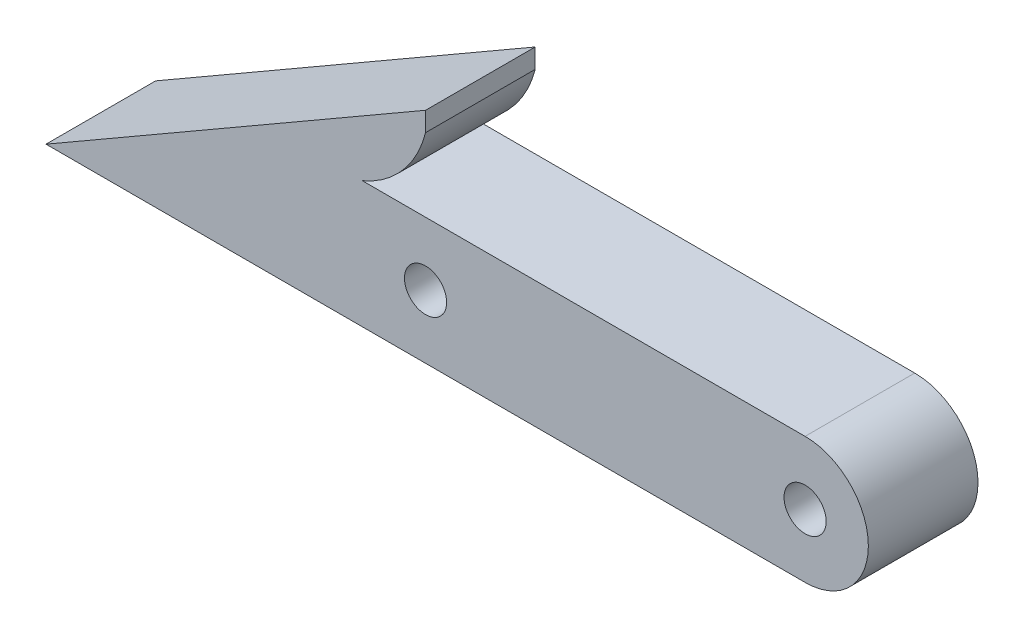
SolidWorks part; units mm, degrees
ref_plane "Front Plane" through (0, 0, 0) normal (0, 0, 1) x (1, 0, 0)
ref_plane "Top Plane" through (0, 0, 0) normal (0, 1, 0) x (1, 0, 0)
ref_plane "Right Plane" through (0, 0, 0) normal (1, 0, 0) x (0, 0, -1)
sketch "Sketch1" plane through (0, 0, 0) normal (0, 0, 1) x (1, 0, 0)
  line L0 (-22.5, 0) -> (22.5, 0)
  line L1 (22.5, 7.5) -> (-22.5, 7.5)
  line L2 (22.5, -7.5) -> (-47.5, -7.5)
  line L4 (-52.5, -7.5) -> (-47.5, -7.5)
  line L5 (-22.5, 7.5) -> (-67.5, 7.5)
  line L6 (-67.5, 7.5) -> (-67.5, -7.5)
  line L7 (-67.5, -7.5) -> (-22.5, -7.5)
  line L8 (-67.5, -7.5) -> (-22.5, 18.4808)
  line L9 (-22.5, 7.5) -> (-22.5, 18.4808)
  line L10 (-22.5, 7.5) -> (-38.5886, 7.5)
  line L11 (-22.5, 7.5) -> (-38.5886, 7.5)
  line L12 (-22.5, 18.4808) -> (-22.5, 16.1808)
  arc A0 (22.5, -7.5) -> (22.5, 7.5) centre (22.5, 0) ccw
  circle A1 centre (-22.5, 0) radius 2.5
  circle A4 centre (22.5, 0) radius 2.5
  arc A5 (-22.5, 7.5) -> (-22.5, -7.5) centre (-22.5, 0) ccw
  arc A6 (-22.5, 16.1808) -> (-30, 7.5) centre (-34.9272, 19.3373) cw
  point P4 (0, 0)
  dimension "D2" = 45
  dimension "D3" = 15
  dimension "D6" = 90
  dimension "D7" = 5
  dimension "D4" = 5
  dimension "D1" = 45
  dimension "D5" = 70
  dimension "D8" = 30
  dimension "D9" = 45
  dimension "D10" = 2.3
extrude "Boss-Extrude1" add sketch "Sketch1" along normal mid plane 13
